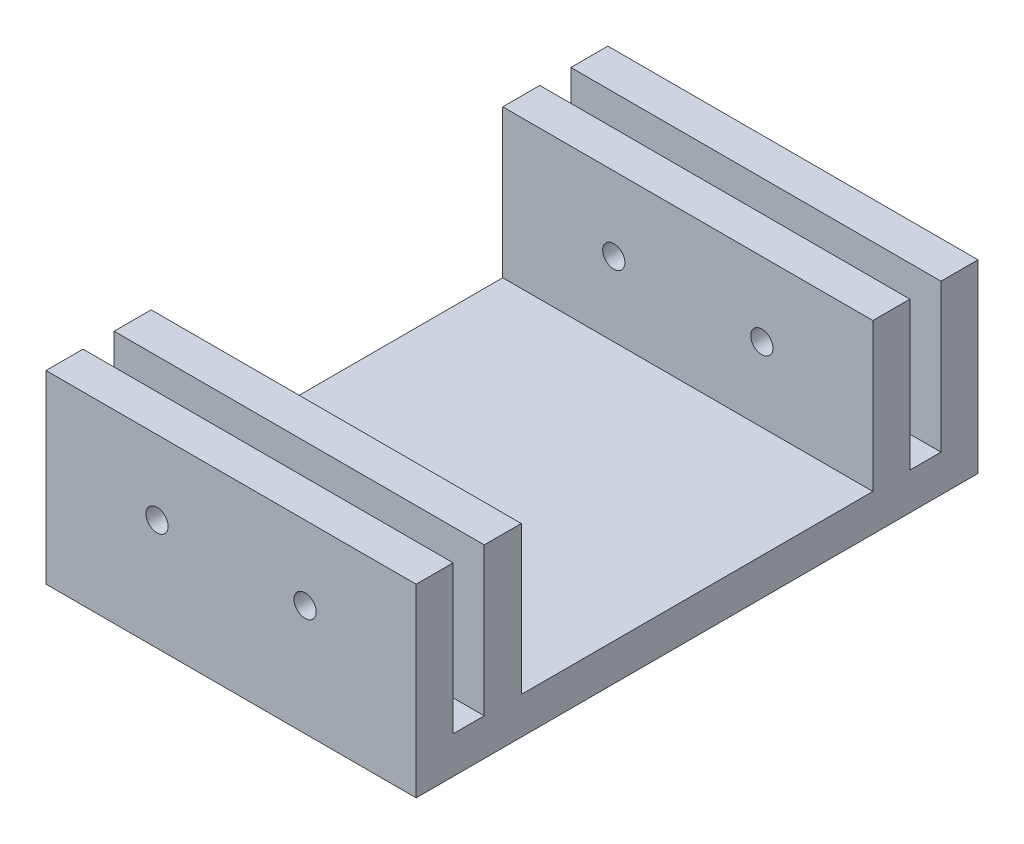
SolidWorks part; units mm, degrees
ref_plane "Alzado" through (0, 0, 0) normal (0, 0, 1) x (1, 0, 0)
ref_plane "Planta" through (0, 0, 0) normal (0, 1, 0) x (1, 0, 0)
ref_plane "Vista lateral" through (0, 0, 0) normal (1, 0, 0) x (0, 0, -1)
sketch "Croquis2" plane through (0, 0, 0) normal (1, 0, 0) x (0, 0, -1)
  line L0 (-34.4182, 2.5) -> (-34.4182, 22.5)
  line L1 (-34.4182, -2.5) -> (41.4818, -2.5)
  line L2 (-34.4182, -2.5) -> (-34.4182, 2.5)
  line L3 (-29.4182, 2.5) -> (-25.2182, 2.5)
  line L4 (41.4818, -2.5) -> (41.4818, 2.5)
  line L5 (-34.4182, -2.5) -> (0, 0) construction
  line L6 (0, 0) -> (41.4818, -2.5) construction
  line L7 (-34.4182, 22.5) -> (-29.4182, 22.5)
  line L8 (-29.4182, 22.5) -> (-29.4182, 2.5)
  line L9 (-25.2182, 2.5) -> (-25.2182, 22.5)
  line L10 (-25.2182, 22.5) -> (-20.2182, 22.5)
  line L11 (-20.2182, 22.5) -> (-20.2182, 2.5)
  line L12 (41.4818, 2.5) -> (41.4818, 22.5)
  line L13 (41.4818, 22.5) -> (36.4818, 22.5)
  line L14 (36.4818, 22.5) -> (36.4818, 2.5)
  line L15 (32.2818, 2.5) -> (32.2818, 22.5)
  line L16 (32.2818, 22.5) -> (27.2818, 22.5)
  line L17 (27.2818, 22.5) -> (27.2818, 2.5)
  line L18 (-20.2182, 2.5) -> (27.2818, 2.5)
  line L19 (32.2818, 2.5) -> (36.4818, 2.5)
  point P0 (0, 0)
  dimension "D1" = 5
  dimension "D2" = 65.9
  dimension "D3" = 5
  dimension "D4" = 20
  dimension "D5" = 20
  dimension "D6" = 5
  dimension "D7" = 4.2
  dimension "D8" = 5
  dimension "D9" = 5
  dimension "D10" = 20
  dimension "D11" = 20
  dimension "D12" = 4.2
extrude "Saliente-Extruir2" add sketch "Croquis2" along normal blind 50
sketch "Croquis3" [suppressed] plane through (0, -2.5, 0) normal (0, -1, 0) x (1, 0, 0)
  line L0 (0, 34.4182) -> (50, -41.4818) construction
  circle A0 centre (25, -3.5318) radius 54.5695
  circle A1 centre (25, -3.5318) radius 40.527
sketch "Croquis4" plane through (0, 0, 34.4182) normal (0, 0, 1) x (1, 0, 0)
  circle A0 centre (15, 12.5) radius 1.5
  circle A1 centre (35, 12.5) radius 1.5
extrude "Cortar-Extruir2" cut sketch "Croquis4" against normal blind 95
